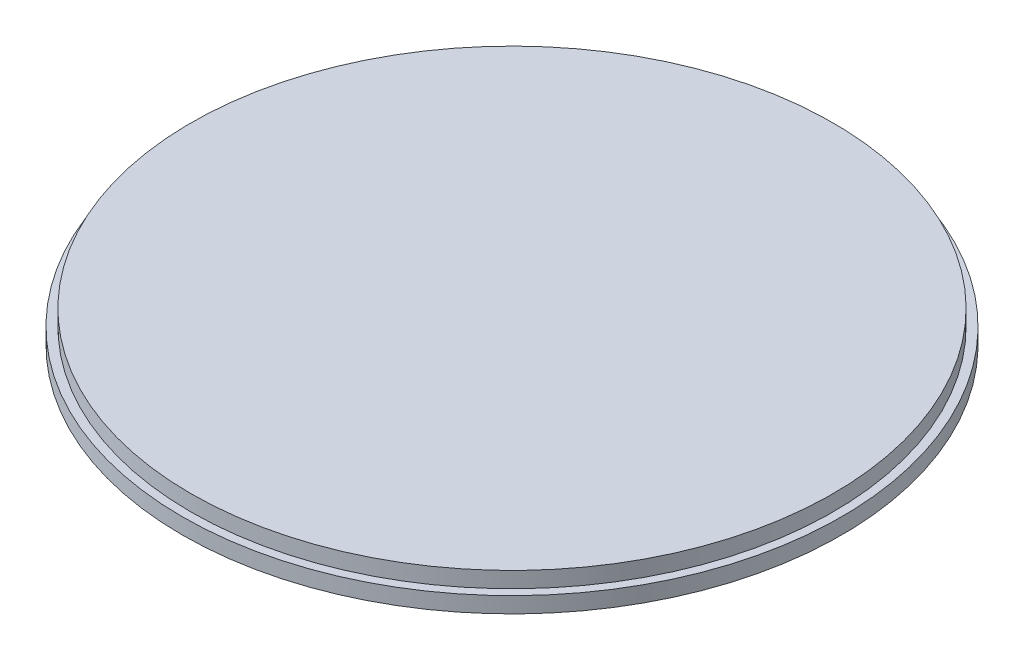
SolidWorks part; units mm, degrees
material "A-Glass Fiber"
ref_plane "Front Plane" through (0, 0, 0) normal (0, 0, 1) x (1, 0, 0)
ref_plane "Top Plane" through (0, 0, 0) normal (0, 1, 0) x (1, 0, 0)
ref_plane "Right Plane" through (0, 0, 0) normal (1, 0, 0) x (0, 0, -1)
sketch "Sketch1" plane through (0, 0, 0) normal (0, 0, 1) x (1, 0, 0)
  line L0 (0, 0) -> (49.53, 0)
  line L1 (49.53, 0) -> (49.53, 2.3813)
  line L2 (49.53, 2.3813) -> (48.26, 2.3813)
  line L3 (48.26, 2.3813) -> (48.26, 4.7625)
  line L4 (48.26, 4.7625) -> (0, 4.7625)
  line L5 (0, 4.7625) -> (0, 0)
  dimension "D1" = 49.53
  dimension "D2" = 48.26
  dimension "D3" = 2.3813
  dimension "D4" = 2.3813
revolve "Revolve1" add sketch "Sketch1" angle 360 about L5
